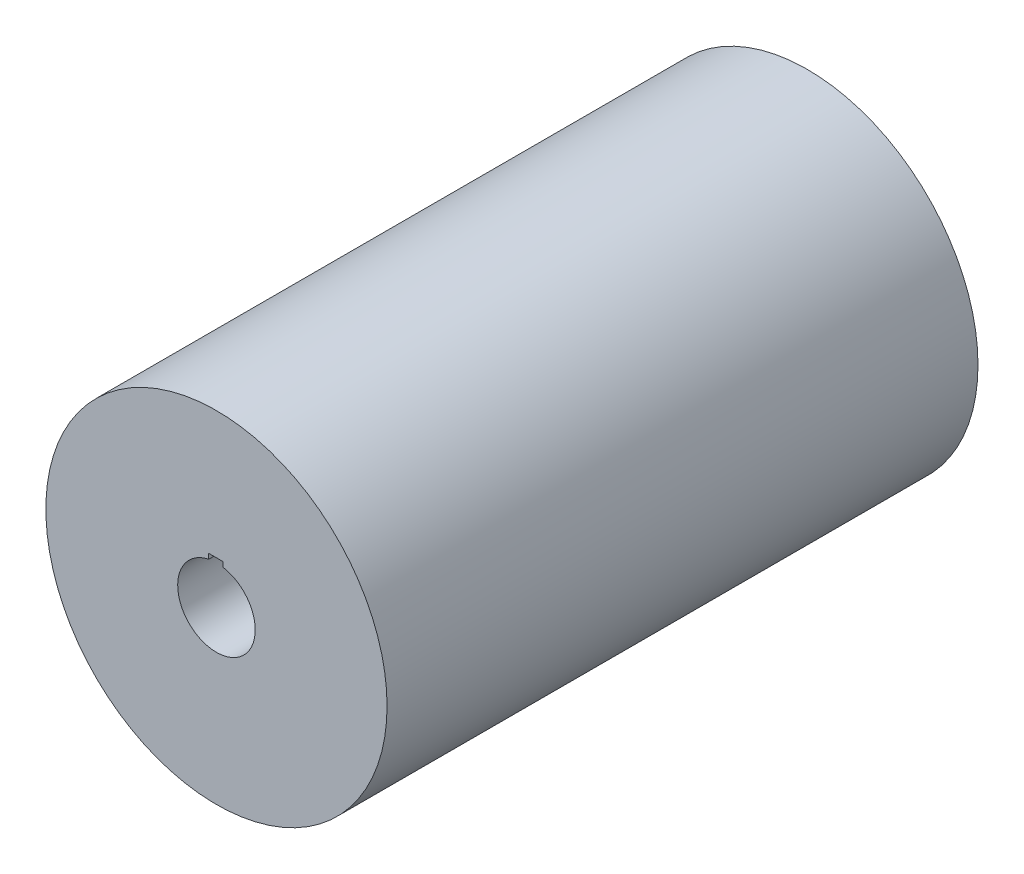
SolidWorks part; units mm, degrees
ref_plane "Front Plane" through (0, 0, 0) normal (0, 0, 1) x (1, 0, 0)
ref_plane "Top Plane" through (0, 0, 0) normal (0, 1, 0) x (1, 0, 0)
ref_plane "Right Plane" through (0, 0, 0) normal (1, 0, 0) x (0, 0, -1)
sketch "Sketch15" plane through (0, 0, 0) normal (0, 0, 1) x (1, 0, 0)
  circle A0 centre (0, 0) radius 11
extrude "Boss-Extrude4" add sketch "Sketch15" along normal blind 50.8
sketch "Sketch16" plane through (0, 0, 0) normal (0, 0, 1) x (1, 0, 0)
  circle A0 centre (0, 0) radius 5
extrude "Cut-Extrude9" cut sketch "Sketch16" against normal blind 50.8 and the other way blind 25.4
ref_plane "Plane4" through (0, 0, 50.8) normal (0, 0, 1) x (1, 0, 0)
sketch "Sketch17" plane through (0, 0, 50.8) normal (0, 0, 1) x (1, 0, 0)
  circle A0 centre (0, 0) radius 2.5
extrude "Cut-Extrude10" cut sketch "Sketch17" against normal blind 25.4
sketch "Sketch20" plane through (0, 0, 50.8) normal (0, 0, 1) x (1, 0, 0)
  line L1 (-0.5, 2.7802) -> (0.4292, 2.7802)
  line L2 (-0.5, 2.7802) -> (-0.5, 2.2167)
  line L3 (-0.5, 2.2167) -> (0.4292, 2.2167)
  line L4 (0.4292, 2.7802) -> (0.4292, 2.2167)
extrude "Cut-Extrude11" cut sketch "Sketch20" against normal blind 25.4 contours L1 L4 L3 L2
sketch "Sketch22" plane through (0, 0, 0) normal (0, 1, 0) x (1, 0, 0)
  circle A0 centre (0, -39.5066) radius 3.175
extrude "Cut-Extrude14" cut sketch "Sketch22" against normal blind 12
ref_plane "Plane8" through (0, -11, 0) normal (0, -1, 0) x (-1, 0, 0)
sketch "Sketch30" plane through (0, -11, 0) normal (0, -1, 0) x (-1, 0, 0)
  circle A0 centre (0, -39.5066) radius 3.175
curve "Helix/Spiral4" pitch 3 height 10.5 turns 3.5
ref_plane "Plane10" through (0, -0.5, 0) normal (0, -1, 0) x (-1, 0, 0)
sketch "Sketch32" plane through (0, -0.5, 0) normal (0, -1, 0) x (-1, 0, 0)
  line L1 (0.5316, -42.6933) -> (-0.2658, -42.2329)
  line L2 (-0.2658, -42.2329) -> (-0.2658, -43.1537)
  line L3 (-0.2658, -43.1537) -> (0.5316, -42.6933)
  circle A0 centre (0, -42.6933) radius 0.2658 construction
sketch "Sketch33" plane through (0, 0, 0) normal (0, 0, 1) x (1, 0, 0)
  circle A0 centre (0, 0) radius 11
extrude "Cut-Extrude15" cut sketch "Sketch33" against normal blind 10 and the other way blind 12.7
